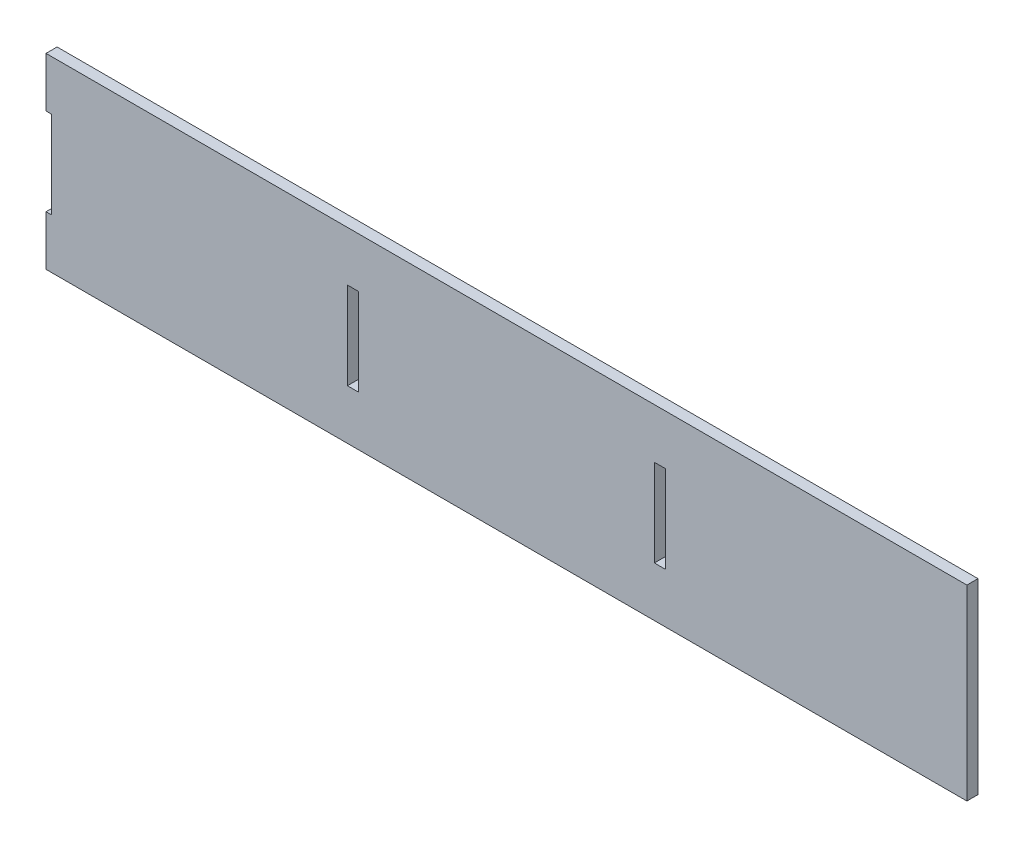
SolidWorks part; units mm, degrees
material "Balsa"
ref_plane "Front" through (0, 0, 0) normal (0, 0, 1) x (1, 0, 0)
ref_plane "Top" through (0, 0, 0) normal (0, 1, 0) x (1, 0, 0)
ref_plane "Right" through (0, 0, 0) normal (1, 0, 0) x (0, 0, -1)
sketch "Sketch1" plane through (0, 0, 0) normal (1, 0, 0) x (0, 0, -1)
  line L0 (612.9211, 24.0273) -> (612.9211, -25.8118) construction
  line L1 (612.9211, 24.8993) -> (612.9211, -28.6308)
  line L2 (616.0961, 24.8993) -> (616.0961, -28.6308)
  line L3 (616.0961, -28.6308) -> (612.9211, -28.6308)
  line L4 (616.0961, 24.8993) -> (612.9211, 24.8993)
  spline S0 degree 3 poles (304.4894, -1963.048) (904.56, -11.0089) (840.5576, -43.532) (789.3572, -23.4586) (777.0615, -18.6436) (760.5817, -13.0401) (739.9968, -7.1233) (715.5772, -0.3798) (687.647, 7.013) (656.6835, 14.9584) (623.1589, 23.2583) (587.5492, 31.6944) (550.3192, 40.0262) (511.9148, 48.0016) (472.7617, 55.3745) (433.2622, 61.9128) (393.7959, 67.4048) (354.7199, 71.6552) (316.357, 74.5357) (278.9313, 75.7536) (242.6994, 75.3938) (207.8706, 73.5467) (174.7468, 70.259) (143.6014, 65.7682) (114.7621, 60.1875) (88.5345, 53.6285) (65.199, 46.2382) (45.0006, 38.1339) (28.1586, 29.5092) (14.871, 20.5578) (6.1442, 12.3133) (1.9481, 6.1765) (0.6391, 3.0841) (0.217, 1.668) (-2.2377, -10.856) (31.8726, -26.5577) (-1993.0578, 155.2139) knots -0.166991 -0.166991 -0.166991 -0.166991 0.003802 0.014472 0.030564 0.051299 0.077028 0.107574 0.142399 0.180921 0.222525 0.266591 0.312515 0.35971 0.407632 0.455773 0.503669 0.550901 0.597096 0.641976 0.685512 0.727353 0.767354 0.805169 0.840471 0.872937 0.902335 0.928425 0.951113 0.970253 0.985871 0.993982 0.996753 0.997907 0.999293 1.04244 1.04244 1.04244 1.04244 only from (802.1511, -28.0117) to (0, 0) construction
  spline S1 degree 3 poles (802.1511, -28.0117) (801.1372, -27.7105) (797.2784, -26.5642) (789.3572, -23.4586) (777.0615, -18.6436) (760.5817, -13.0401) (739.9968, -7.1233) (715.5772, -0.3798) (687.647, 7.013) (656.6835, 14.9584) (623.1589, 23.2583) (587.5492, 31.6944) (550.3192, 40.0262) (511.9148, 48.0016) (472.7617, 55.3745) (433.2622, 61.9128) (393.7959, 67.4048) (354.7199, 71.6552) (316.357, 74.5357) (278.9313, 75.7536) (242.6994, 75.3938) (207.8706, 73.5467) (174.7468, 70.259) (143.6014, 65.7682) (114.7621, 60.1875) (88.5345, 53.6285) (65.199, 46.2382) (45.0006, 38.1339) (28.1586, 29.5092) (14.871, 20.5578) (6.1442, 12.3133) (1.9481, 6.1765) (0.6391, 3.0841) (0.217, 1.668) (0.0426, 0.7778) (0.0107, 0.1963) (0, 0) knots 0 0 0 0 0.003802 0.014472 0.030564 0.051299 0.077028 0.107574 0.142399 0.180921 0.222525 0.266591 0.312515 0.35971 0.407632 0.455773 0.503669 0.550901 0.597096 0.641976 0.685512 0.727353 0.767354 0.805169 0.840471 0.872937 0.902335 0.928425 0.951113 0.970253 0.985871 0.993982 0.996753 0.997907 0.999293 1 1 1 1 construction
  spline S2 degree 3 poles (-1994.7901, -130.8385) (49.5083, 45.0487) (-3.9103, 18.1854) (0.5702, -4.3968) (2.5361, -10.6164) (7.9982, -20.5501) (16.1137, -34.185) (25.7513, -48.9002) (36.932, -62.9388) (49.3364, -75.9186) (65.2269, -85.625) (84.4528, -91.7174) (106.8521, -96.1515) (132.5109, -98.5722) (161.1944, -99.0924) (192.7613, -97.7042) (227.0382, -94.5118) (263.8348, -89.6638) (302.9215, -83.3884) (344.0178, -75.9778) (386.7768, -67.7807) (430.7746, -59.2023) (475.4963, -50.6638) (520.3353, -42.6036) (564.5889, -35.4228) (607.4709, -29.4733) (648.1275, -25.0145) (685.6676, -22.1862) (719.1968, -21.0048) (747.8303, -21.2786) (770.6884, -22.8547) (787.0914, -25.0735) (855.7552, -37.3672) (910.4178, -89.1553) (1388.6423, 1880.9845) knots -0.071347 -0.071347 -0.071347 -0.071347 0.001821 0.004613 0.009135 0.024676 0.044153 0.064937 0.086321 0.107138 0.1276 0.150893 0.177565 0.207668 0.241222 0.278203 0.318526 0.362031 0.408465 0.457479 0.508614 0.561296 0.614835 0.668438 0.721214 0.772202 0.820393 0.864766 0.904324 0.938132 0.965242 0.98469 0.99621 1.210002 1.210002 1.210002 1.210002 only from (0, 0) to (802.1511, -28.0117) construction
  spline S3 degree 3 poles (0, 0) (0.0175, -0.519) (0.0617, -1.8338) (0.5702, -4.3968) (2.5361, -10.6164) (7.9982, -20.5501) (16.1137, -34.185) (25.7513, -48.9002) (36.932, -62.9388) (49.3364, -75.9186) (65.2269, -85.625) (84.4528, -91.7174) (106.8521, -96.1515) (132.5109, -98.5722) (161.1944, -99.0924) (192.7613, -97.7042) (227.0382, -94.5118) (263.8348, -89.6638) (302.9215, -83.3884) (344.0178, -75.9778) (386.7768, -67.7807) (430.7746, -59.2023) (475.4963, -50.6638) (520.3353, -42.6036) (564.5889, -35.4228) (607.4709, -29.4733) (648.1275, -25.0145) (685.6676, -22.1862) (719.1968, -21.0048) (747.8303, -21.2786) (770.6884, -22.8547) (787.0914, -25.0735) (796.8423, -26.8193) (801.0977, -27.7751) (802.1511, -28.0117) knots 0 0 0 0 0.001821 0.004613 0.009135 0.024676 0.044153 0.064937 0.086321 0.107138 0.1276 0.150893 0.177565 0.207668 0.241222 0.278203 0.318526 0.362031 0.408465 0.457479 0.508614 0.561296 0.614835 0.668438 0.721214 0.772202 0.820393 0.864766 0.904324 0.938132 0.965242 0.98469 0.99621 1 1 1 1 construction
  dimension "D1" = 3.175
extrude "Boss-Extrude1" add sketch "Sketch1" along normal up to surface (263.525 mm away) contours L2 L4 L1 L3
sketch "Sketch5" plane through (0, 0, -612.9211) normal (0, 0, 1) x (1, 0, 0)
  line L1 (-1.5875, 10.6118) -> (1.5875, 10.6118)
  line L2 (-1.5875, 10.6118) -> (-1.5875, -14.3433)
  line L3 (-1.5875, -14.3433) -> (1.5875, -14.3433)
  line L4 (1.5875, 10.6118) -> (1.5875, -14.3433)
  line L5 (263.525, 24.8993) -> (0, 24.8993) construction
  line L6 (263.525, -28.6308) -> (0, -28.6308) construction
  line L9 (0, 24.8993) -> (0, -28.6308) construction
  point P10 (0, 10.6118)
  dimension "D1" = 14.2875
  dimension "D2" = 14.2875
  dimension "D3" = 3.175
extrude "Cut-Extrude1" cut sketch "Sketch5" against normal through all both and the other way through all
pattern_linear "LPattern1" count 4 spacing 87.8417 along (1, 0, 0) skipping (3, 0) of "Cut-Extrude1"
